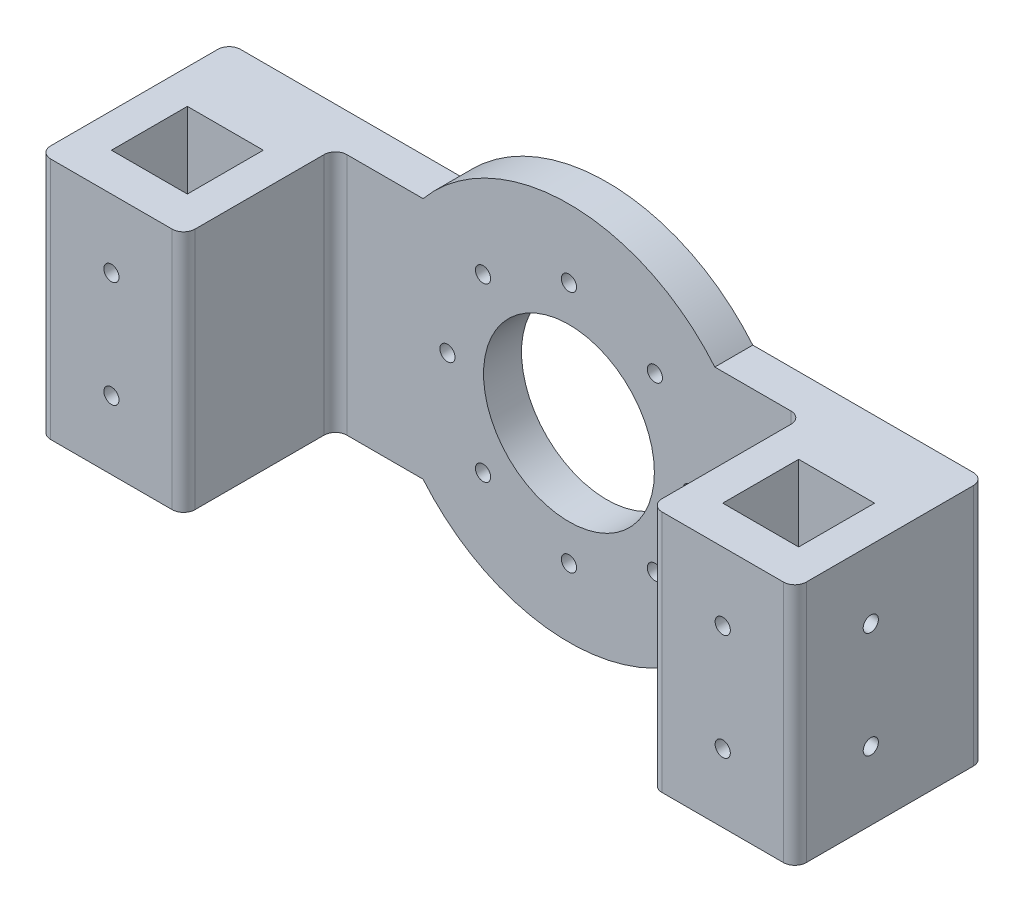
SolidWorks part; units mm, degrees
ref_plane "Front Plane" through (0, 0, 0) normal (0, 0, 1) x (1, 0, 0)
ref_plane "Top Plane" through (0, 0, 0) normal (0, 1, 0) x (1, 0, 0)
ref_plane "Right Plane" through (0, 0, 0) normal (1, 0, 0) x (0, 0, -1)
sketch "Sketch1" plane through (0, 0, 0) normal (0, 0, 1) x (1, 0, 0)
  line L0 (38.4187, 32) -> (99.5, 32)
  line L1 (-99.5, -32) -> (-38.4187, -32)
  line L2 (-99.5, -32) -> (-99.5, 32)
  line L3 (-99.5, 32) -> (-38.4187, 32)
  line L4 (99.5, -32) -> (99.5, 32)
  line L5 (-99.5, -32) -> (99.5, 32) construction
  line L6 (-99.5, 32) -> (99.5, -32) construction
  line L7 (38.4187, -32) -> (99.5, -32)
  circle A0 centre (0, 0) radius 32 construction
  arc A1 (-38.4187, -32) -> (38.4187, -32) centre (0, 0) ccw
  arc A2 (38.4187, 32) -> (-38.4187, 32) centre (0, 0) ccw
  dimension "D1" = 64
  dimension "D2" = 100
  dimension "D3" = 64
  dimension "D4" = 199
extrude "Boss-Extrude1" add sketch "Sketch1" along normal blind 10
sketch "Sketch2" plane through (0, 0, 10) normal (0, 0, 1) x (1, 0, 0)
  circle A0 centre (0, 0) radius 22.5
  dimension "D1" = 45
extrude "Cut-Extrude1" cut sketch "Sketch2" against normal through all
sketch "Sketch3" plane through (0, 0, 10) normal (0, 0, 1) x (1, 0, 0)
  line L0 (0, 0) -> (39.5441, 0) construction
  circle A0 centre (0, 0) radius 32 construction
  circle A1 centre (32, 0) radius 2
  circle A2 centre (22.6274, -22.6274) radius 2
  circle A3 centre (0, -32) radius 2
  circle A4 centre (-22.6274, -22.6274) radius 2
  circle A5 centre (-32, 0) radius 2
  circle A6 centre (-22.6274, 22.6274) radius 2
  circle A7 centre (0, 32) radius 2
  circle A8 centre (22.6274, 22.6274) radius 2
  point P22 (0, 0)
  dimension "D1" = 64
  dimension "D2" = 4
  dimension "D3" = 8
extrude "Cut-Extrude2" cut sketch "Sketch3" against normal through all
sketch "Sketch5" plane through (0, 0, 10) normal (0, 0, 1) x (1, 0, 0)
  line L0 (38.4187, -32) -> (99.5, -32) construction
  line L1 (99.5, 32) -> (61.5, 32)
  line L2 (99.5, 32) -> (99.5, -32)
  line L3 (99.5, -32) -> (61.5, -32)
  line L4 (61.5, 32) -> (61.5, -32)
  line L5 (0, 0) -> (127.4397, 0) construction
  line L6 (80.5, 32) -> (80.5, -32) construction
  line L7 (0, 57.1591) -> (0, -67.9439) construction
  line L8 (-99.5, -32) -> (-61.5, -32)
  line L9 (-61.5, 32) -> (-61.5, -32)
  line L10 (-99.5, 32) -> (-61.5, 32)
  line L11 (-99.5, 32) -> (-99.5, -32)
  dimension "D1" = 61.5
extrude "Boss-Extrude2" add sketch "Sketch5" along normal blind 40 contours L2 L1 L4 L3 | L8 L9 L10 L11
sketch "Sketch6" plane through (0, 32, 0) normal (0, 1, 0) x (1, 0, 0)
  line L0 (61.5, -30) -> (103.893, -30) construction
  line L1 (61.5, -50) -> (61.5, -10) construction
  line L3 (80.5, 5.0175) -> (80.5, -58.0732) construction
  line L4 (99.5, -50) -> (99.5, 0) construction
  line L7 (0, 16.5213) -> (0, -70.6554) construction
  line L8 (70.5, -40) -> (90.5, -40)
  line L9 (70.5, -40) -> (70.5, -20)
  line L10 (70.5, -20) -> (90.5, -20)
  line L11 (90.5, -40) -> (90.5, -20)
  line L12 (70.5, -40) -> (90.5, -20) construction
  line L13 (70.5, -20) -> (90.5, -40) construction
  line L14 (-70.5, -20) -> (-90.5, -20)
  line L15 (-90.5, -40) -> (-90.5, -20)
  line L16 (-70.5, -40) -> (-90.5, -40)
  line L17 (-70.5, -40) -> (-70.5, -20)
  point P12 (80.5, -30)
  dimension "D1" = 19
  dimension "D2" = 20
  dimension "D3" = 20
extrude "Cut-Extrude3" cut sketch "Sketch6" against normal through all
sketch "Sketch8" plane through (0, 0, 50) normal (0, 0, 1) x (1, 0, 0)
  line L0 (80.5, 32) -> (80.5, -32) construction
  line L1 (99.5, 32) -> (61.5, 32) construction
  line L2 (99.5, -32) -> (61.5, -32) construction
  line L3 (0, 57.8781) -> (0, -64.1692) construction
  circle A1 centre (80.5, 14) radius 2
  circle A2 centre (80.5, -14) radius 2
  circle A3 centre (-80.5, -14) radius 2
  circle A4 centre (-80.5, 14) radius 2
  dimension "D1" = 4
  dimension "D2" = 4
  dimension "D3" = 18
  dimension "D4" = 18
extrude "Cut-Extrude4" cut sketch "Sketch8" against normal up to next and the other way through all
sketch "Sketch9" plane through (99.5, 0, 0) normal (1, 0, 0) x (0, 0, -1)
  line L0 (-30, 32) -> (-30, -33.4307) construction
  line L1 (-50, 32) -> (0, 32) construction
  line L2 (-50, -32) -> (0, -32) construction
  line L3 (-50, 32) -> (-50, -32) construction
  circle A0 centre (-30, 14) radius 2
  circle A1 centre (-30, -14) radius 2
  dimension "D1" = 4
  dimension "D2" = 4
  dimension "D3" = 18
  dimension "D4" = 18
  dimension "D5" = 20
extrude "Cut-Extrude5" cut sketch "Sketch9" against normal up to next
sketch "Sketch10" plane through (-99.5, 0, 0) normal (-1, 0, 0) x (0, 0, 1)
  line L0 (30, 32) -> (30, -32) construction
  line L1 (50, 32) -> (0, 32) construction
  line L2 (50, -32) -> (0, -32) construction
  line L3 (50, 32) -> (50, -32) construction
  circle A0 centre (30, 14) radius 2
  circle A1 centre (30, -14) radius 2
  dimension "D2" = 4
  dimension "D3" = 4
  dimension "D1" = 20
  dimension "D4" = 18
  dimension "D5" = 18
extrude "Cut-Extrude6" cut sketch "Sketch10" against normal up to next
fillet "Fillet1" radius 3 2 edges at (61.5, 0, 10) (-61.5, 0, 10)
fillet "Fillet2" radius 3 4 edges at (99.5, 0, 50) (61.5, 0, 50) (-99.5, 0, 50) (-61.5, 0, 50)
fillet "Fillet3" radius 3 2 edges at (99.5, 0, 0) (-99.5, 0, 0)
